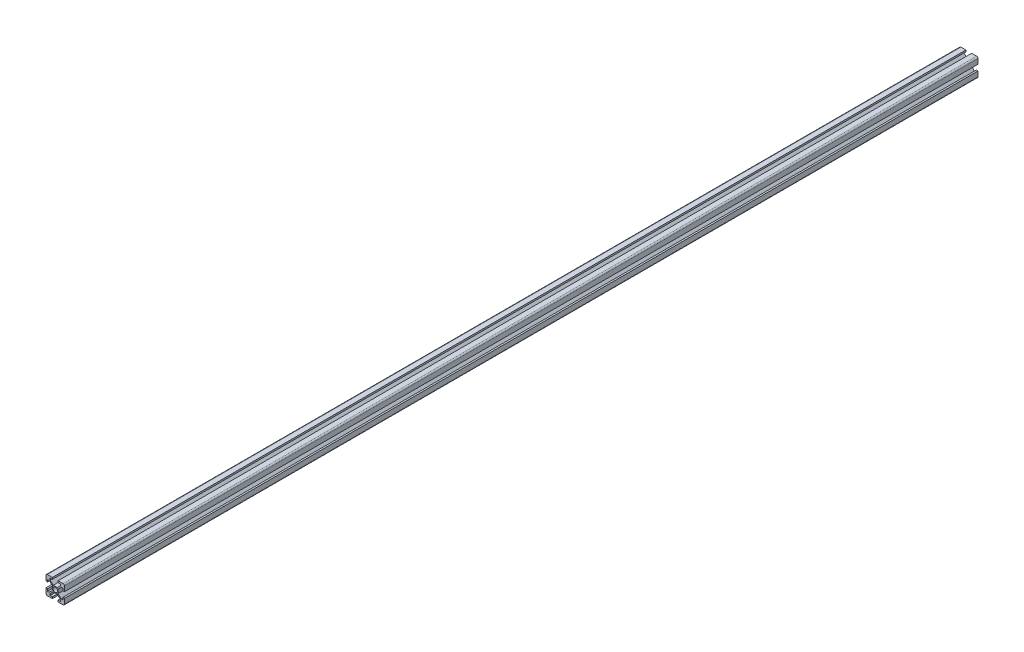
SolidWorks part; units mm, degrees
ref_plane "前视基准面" through (0, 0, 0) normal (0, 0, 1) x (1, 0, 0)
ref_plane "上视基准面" through (0, 0, 0) normal (0, 1, 0) x (1, 0, 0)
ref_plane "右视基准面" through (0, 0, 0) normal (1, 0, 0) x (0, 0, -1)
sketch "草图1" plane through (0, 0, 0) normal (0, 0, 1) x (1, 0, 0)
  line L0 (-10, -3.1) -> (-8.2, -3.1)
  line L1 (-8.5, 10) -> (8.5, 10)
  line L2 (-10, 8.5) -> (-10, -8.5)
  line L3 (-8.5, -10) -> (8.5, -10)
  line L4 (10, 8.5) -> (10, -8.5)
  line L5 (-10, 10) -> (10, -10) construction
  line L6 (-10, -10) -> (10, 10) construction
  line L7 (-3.0541, 3.1) -> (3.0541, 3.1)
  line L8 (-3.0541, 3.1) -> (-3.0541, -3.1)
  line L9 (-3.0541, -3.1) -> (3.0541, -3.1)
  line L10 (3.0541, 3.1) -> (3.0541, -3.1)
  line L11 (-3.0541, 3.1) -> (3.0541, -3.1) construction
  line L12 (-3.0541, -3.1) -> (3.0541, 3.1) construction
  line L13 (-8.2, -3.1) -> (-8.2, -5.5)
  line L14 (-8.2, -5.5) -> (-6.3971, -5.5)
  line L15 (-6.3971, -5.5) -> (-3.0541, -2.1571)
  line L16 (-5.5, 6.3971) -> (-2.1571, 3.0541)
  line L17 (-5.5, 8.2) -> (-5.5, 6.3971)
  line L18 (-3.1, 8.2) -> (-5.5, 8.2)
  line L19 (-3.1, 10) -> (-3.1, 8.2)
  line L20 (6.3971, 5.5) -> (3.0541, 2.1571)
  line L21 (8.2, 5.5) -> (6.3971, 5.5)
  line L22 (8.2, 3.1) -> (8.2, 5.5)
  line L23 (10, 3.1) -> (8.2, 3.1)
  line L24 (5.5, -6.3971) -> (2.1571, -3.0541)
  line L25 (5.5, -8.2) -> (5.5, -6.3971)
  line L26 (3.1, -8.2) -> (5.5, -8.2)
  line L27 (3.1, -10) -> (3.1, -8.2)
  line L28 (-3.1, -10) -> (-3.1, -8.2)
  line L29 (-3.1, -8.2) -> (-5.5, -8.2)
  line L30 (-5.5, -8.2) -> (-5.5, -6.3971)
  line L31 (-5.5, -6.3971) -> (-2.1571, -3.0541)
  line L32 (-8.2, 5.5) -> (-6.3971, 5.5)
  line L33 (-6.3971, 5.5) -> (-3.0541, 2.1571)
  line L34 (-8.2, 3.1) -> (-8.2, 5.5)
  line L35 (-10, 3.1) -> (-8.2, 3.1)
  line L36 (5.5, 8.2) -> (5.5, 6.3971)
  line L37 (5.5, 6.3971) -> (2.1571, 3.0541)
  line L38 (3.1, 8.2) -> (5.5, 8.2)
  line L39 (3.1, 10) -> (3.1, 8.2)
  line L40 (8.2, -5.5) -> (6.3971, -5.5)
  line L41 (6.3971, -5.5) -> (3.0541, -2.1571)
  line L42 (8.2, -3.1) -> (8.2, -5.5)
  line L43 (10, -3.1) -> (8.2, -3.1)
  circle A0 centre (0, 0) radius 2.5
  arc A1 (-10, 8.5) -> (-8.5, 10) centre (-8.5, 8.5) cw
  arc A2 (-10, -8.5) -> (-8.5, -10) centre (-8.5, -8.5) ccw
  arc A3 (8.5, 10) -> (10, 8.5) centre (8.5, 8.5) cw
  arc A4 (10, -8.5) -> (8.5, -10) centre (8.5, -8.5) cw
  point P0 (0, 0)
  point P20 (0, 0)
  point P26 (0, 0)
  point P32 (0, 0)
  point P38 (0, 0)
  point P60 (0, 0)
  dimension "D1" = 4
  dimension "D3" = 1.5
  dimension "D4" = 1.5
  dimension "D5" = 1.5
  dimension "D2" = 4
extrude "凸台-拉伸1" add sketch "草图1" along normal blind 990
